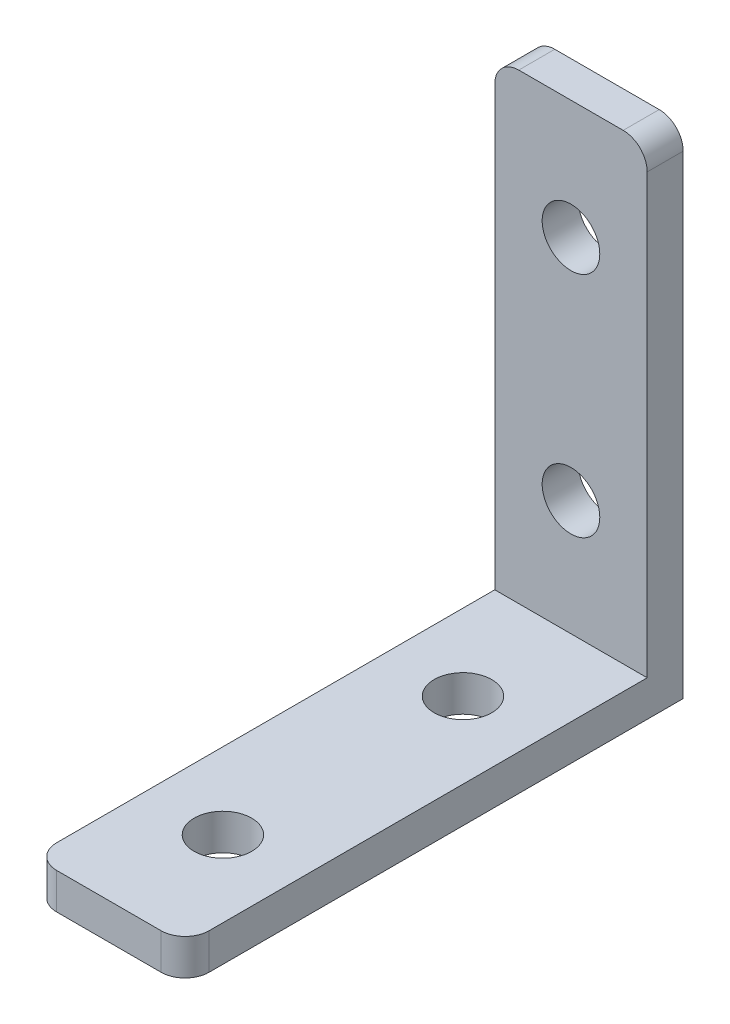
SolidWorks part; units mm, degrees
material "Gerais  - 6061-T6"
ref_plane "Plano frontal" through (0, 0, 0) normal (0, 0, 1) x (1, 0, 0)
ref_plane "Plano superior" through (0, 0, 0) normal (0, 1, 0) x (1, 0, 0)
ref_plane "Plano direito" through (0, 0, 0) normal (1, 0, 0) x (0, 0, -1)
sketch "Esboço1" plane through (0, 0, 0) normal (0, 0, 1) x (1, 0, 0)
  line L1 (-6.35, -20.75) -> (6.35, -20.75)
  line L2 (-6.35, -20.75) -> (-6.35, 20.75)
  line L3 (-6.35, 20.75) -> (6.35, 20.75)
  line L4 (6.35, -20.75) -> (6.35, 20.75)
  line L5 (0, 20.75) -> (0, -20.75) construction
  line L6 (-6.35, 0) -> (6.35, 0) construction
  circle A0 centre (0, 10.85) radius 2.4
  circle A1 centre (0, -8.15) radius 2.4
  point P0 (0, 0)
  dimension "D1" = 4.8
  dimension "D2" = 19
  dimension "D3" = 12.6
  dimension "D4" = 41.5
  dimension "D5" = 12.7
extrude "Ressalto-extrusão1" add sketch "Esboço1" along normal blind 3
sketch "Esboço2" plane through (0, 0, 3) normal (0, 0, 1) x (1, 0, 0)
  line L0 (-6.35, -20.75) -> (6.35, -20.75) construction
  line L1 (6.35, -17.75) -> (-6.35, -17.75)
  line L2 (6.35, -17.75) -> (6.35, -20.75)
  line L3 (6.35, -20.75) -> (-6.35, -20.75)
  line L4 (-6.35, -17.75) -> (-6.35, -20.75)
  line L5 (0, -20.75) -> (0, -17.75) construction
  line L6 (6.35, -19.25) -> (-6.35, -19.25) construction
  point P0 (0, -19.25)
  point P4 (6.2748, -20.75)
  point P5 (4.1117, -20.75)
  dimension "D1" = 3
extrude "Ressalto-extrusão2" add sketch "Esboço2" along normal blind 38.5 contours L1 L4 L3 L2
sketch "Esboço3" plane through (0, -17.75, 0) normal (0, 1, 0) x (1, 0, 0)
  line L0 (6.35, -41.5) -> (-6.35, -41.5) construction
  line L2 (-6.35, 0) -> (6.35, 0) construction
  circle A0 centre (0, -12) radius 2.4
  circle A1 centre (0, -32) radius 2.4
  point P4 (0, -12.6635)
  point P5 (0, -41.5)
  point P6 (-11.4915, 0)
  point P9 (0, 0)
  dimension "D1" = 4.8
  dimension "D3" = 20
  dimension "D2" = 12
extrude "Corte-extrusão1" cut sketch "Esboço3" against normal blind 41.5 contours A0 | A1
fillet "Filete1" radius 2 4 edges at (-6.35, 20.75, 1.5) (6.35, 20.75, 1.5) (-6.35, -19.25, 41.5) (6.35, -19.25, 41.5)
